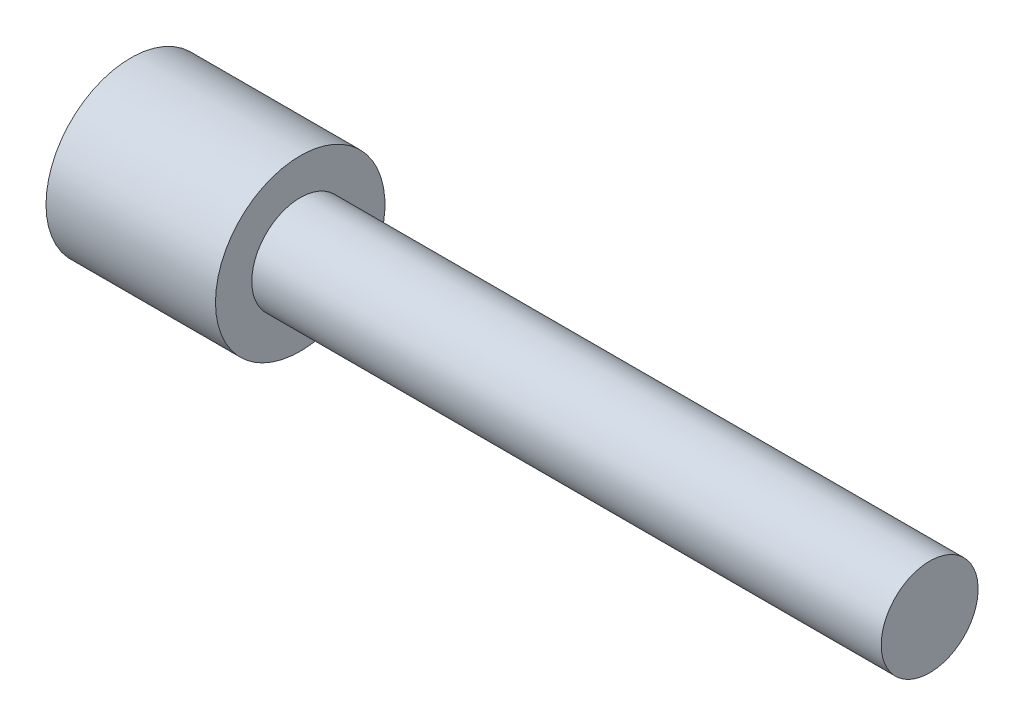
SolidWorks part; units mm, degrees
ref_plane "Front Plane" through (0, 0, 0) normal (0, 0, 1) x (1, 0, 0)
ref_plane "Top Plane" through (0, 0, 0) normal (0, 1, 0) x (1, 0, 0)
ref_plane "Right Plane" through (0, 0, 0) normal (1, 0, 0) x (0, 0, -1)
sketch "Sketch1" plane through (0, 0, 0) normal (0, 0, 1) x (1, 0, 0)
  line L0 (0, 0) -> (13.1988, 0)
  line L1 (13.1988, 0) -> (13.1988, 1)
  line L2 (13.1988, 1) -> (0.1988, 1)
  line L3 (0.1988, 1) -> (0.1988, 1.75)
  line L4 (0.1988, 1.75) -> (-3.3012, 1.75)
  line L5 (-3.3012, 1.75) -> (-3.3012, 0)
  line L6 (-3.3012, 0) -> (0, 0)
  dimension "D1" = 1
  dimension "D2" = 1.75
  dimension "D3" = 3.5
  dimension "D4" = 13
revolve "Revolve1" add sketch "Sketch1" angle 360 about L6
